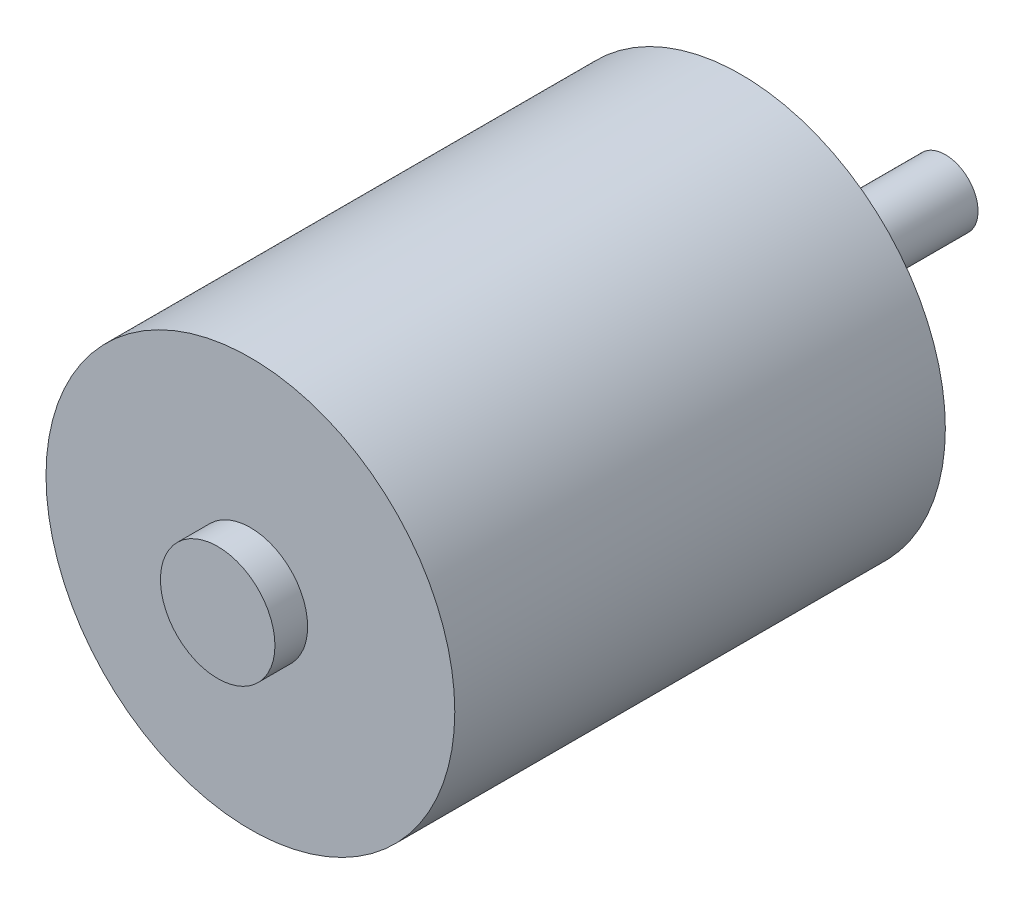
SolidWorks part; units mm, degrees
ref_plane "Front Plane" through (0, 0, 0) normal (0, 0, 1) x (1, 0, 0)
ref_plane "Top Plane" through (0, 0, 0) normal (0, 1, 0) x (1, 0, 0)
ref_plane "Right Plane" through (0, 0, 0) normal (1, 0, 0) x (0, 0, -1)
sketch "Sketch1" plane through (0, 0, 0) normal (0, 0, 1) x (1, 0, 0)
  circle A0 centre (0, 0) radius 25
  dimension "D1" = 50
extrude "Boss-Extrude1" add sketch "Sketch1" along normal blind 7 contours A0
ref_plane "Plane1" through (0, 0, 0) normal (0, 0, -1) x (-1, 0, 0)
sketch "Sketch2" plane through (0, 0, 0) normal (0, 0, -1) x (-1, 0, 0)
  line L0 (0, 0) -> (0, 4) construction
  line L1 (0, 0) -> (4, 0) construction
  circle A0 centre (0, 0) radius 4
  dimension "D1" = 8
extrude "Boss-Extrude3" add sketch "Sketch2" along normal blind 25 contours A0
ref_plane "Plane2" through (0, 0, 7) normal (0, 0, 1) x (1, 0, 0)
sketch "Sketch3" plane through (0, 0, 7) normal (0, 0, 1) x (1, 0, 0)
  circle A0 centre (0, 0) radius 25
extrude "Boss-Extrude4" add sketch "Sketch3" along normal blind 53
ref_plane "Plane3" through (0, 0, 60) normal (0, 0, 1) x (1, 0, 0)
sketch "Sketch4" plane through (0, 0, 60) normal (0, 0, 1) x (1, 0, 0)
  circle A0 centre (0, 0) radius 7
  dimension "D1" = 14
extrude "Boss-Extrude5" add sketch "Sketch4" along normal blind 4 contours A0
